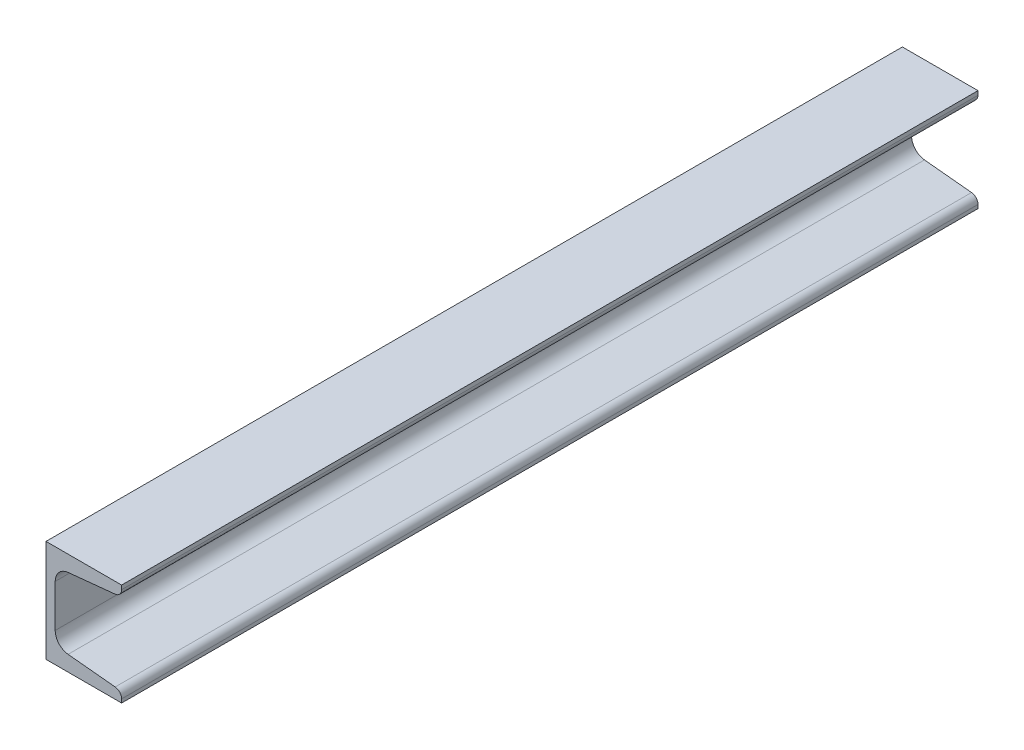
SolidWorks part; units mm, degrees
ref_plane "前视基准面" through (0, 0, 0) normal (0, 0, 1) x (1, 0, 0)
ref_plane "上视基准面" through (0, 0, 0) normal (0, 1, 0) x (1, 0, 0)
ref_plane "右视基准面" through (0, 0, 0) normal (1, 0, 0) x (0, 0, -1)
sketch "草图1" plane through (0, 0, 0) normal (0, 0, 1) x (1, 0, 0)
  line L0 (0, 0) -> (0, 50)
  line L1 (0, 0) -> (37, 0)
  line L2 (-55.9537, 25) -> (55.9537, 25) construction
  line L3 (0, 50) -> (37, 50)
  line L4 (4.5, 14.5099) -> (4.5, 35.2876)
  line L5 (16.25, -10) -> (16.25, 60) construction
  line L6 (10.8035, 7.5447) -> (33.8483, 5.2402)
  line L7 (37, 0) -> (37, 1.7575)
  line L8 (10.8035, 42.2529) -> (33.8483, 44.5574)
  line L9 (37, 48.04) -> (37, 50)
  arc A0 (10.8035, 42.2529) -> (4.5, 35.2876) centre (11.5, 35.2876) ccw
  arc A1 (4.5, 14.5099) -> (10.8035, 7.5447) centre (11.5, 14.5099) ccw
  arc A2 (33.8483, 44.5574) -> (37, 48.04) centre (33.5, 48.04) ccw
  arc A3 (37, 1.7575) -> (33.8483, 5.2402) centre (33.5, 1.7575) ccw
  point P7 (0, 25)
  point P11 (4.5, 25)
  point P14 (16.25, 25)
  point P15 (16.25, 7)
  point P17 (16.25, 43)
  point P19 (16.25, 43)
  point P20 (16.25, 7)
  point P23 (16.25, 43)
  dimension "D5" = 7
  dimension "D6" = 7
  dimension "D7" = 3.5
  dimension "D8" = 3.5
  dimension "h" = 50
  dimension "b" = 37
  dimension "d" = 4.5
  dimension "D1" = 16.25
  dimension "D2" = 7
  dimension "D3" = 5.711
  dimension "D4" = 5.711
extrude "凸台-拉伸1" add sketch "草图1" along normal blind 419
equation "\"高度\"= 50"
equation "\"腿宽\"= 37"
equation "\"腰宽\"= 4.5"
equation "\"h@草图1\"= \"高度\""
equation "\"d@草图1\"= \"腰宽\""
equation "\"D1@草图1\"= ( \"腿宽\" - \"腰宽\" ) / 2"
equation "\"平均腿厚\"= 7"
equation "\"内圆弧半径\"= 7"
equation "\"腿端圆弧半径\"= 3.5"
equation "\"D2@草图1\"= \"平均腿厚\""
equation "\"斜度\"= atn ( 0.1 )"
equation "\"D3@草图1\"= \"斜度\""
equation "\"D4@草图1\"= \"斜度\""
equation "\"D5@草图1\"= \"内圆弧半径\""
equation "\"D6@草图1\"= \"内圆弧半径\""
equation "\"D8@草图1\"= \"腿端圆弧半径\""
equation "\"D7@草图1\"= \"腿端圆弧半径\""
equation "\"b@草图1\"= \"腿宽\""
